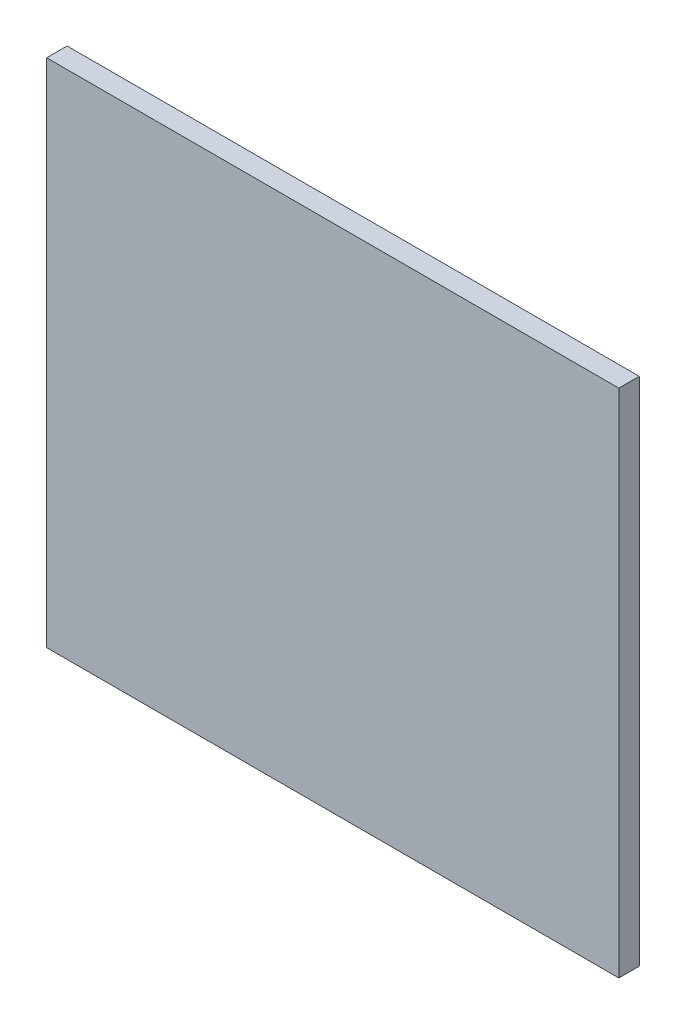
SolidWorks part; units mm, degrees
ref_plane "Front Plane" through (0, 0, 0) normal (0, 0, 1) x (1, 0, 0)
ref_plane "Top Plane" through (0, 0, 0) normal (0, 1, 0) x (1, 0, 0)
ref_plane "Right Plane" through (0, 0, 0) normal (1, 0, 0) x (0, 0, -1)
sketch "Sketch1" plane through (0, 0, 0) normal (0, 0, 1) x (1, 0, 0)
  line L1 (-88.9, -79.375) -> (88.9, -79.375)
  line L2 (-88.9, -79.375) -> (-88.9, 79.375)
  line L3 (-88.9, 79.375) -> (88.9, 79.375)
  line L4 (88.9, -79.375) -> (88.9, 79.375)
  line L5 (-88.9, -79.375) -> (88.9, 79.375) construction
  line L6 (-88.9, 79.375) -> (88.9, -79.375) construction
  point P0 (0, 0)
  dimension "D1" = 177.8
  dimension "D2" = 158.75
extrude "Boss-Extrude1" add sketch "Sketch1" along normal blind 6.35
